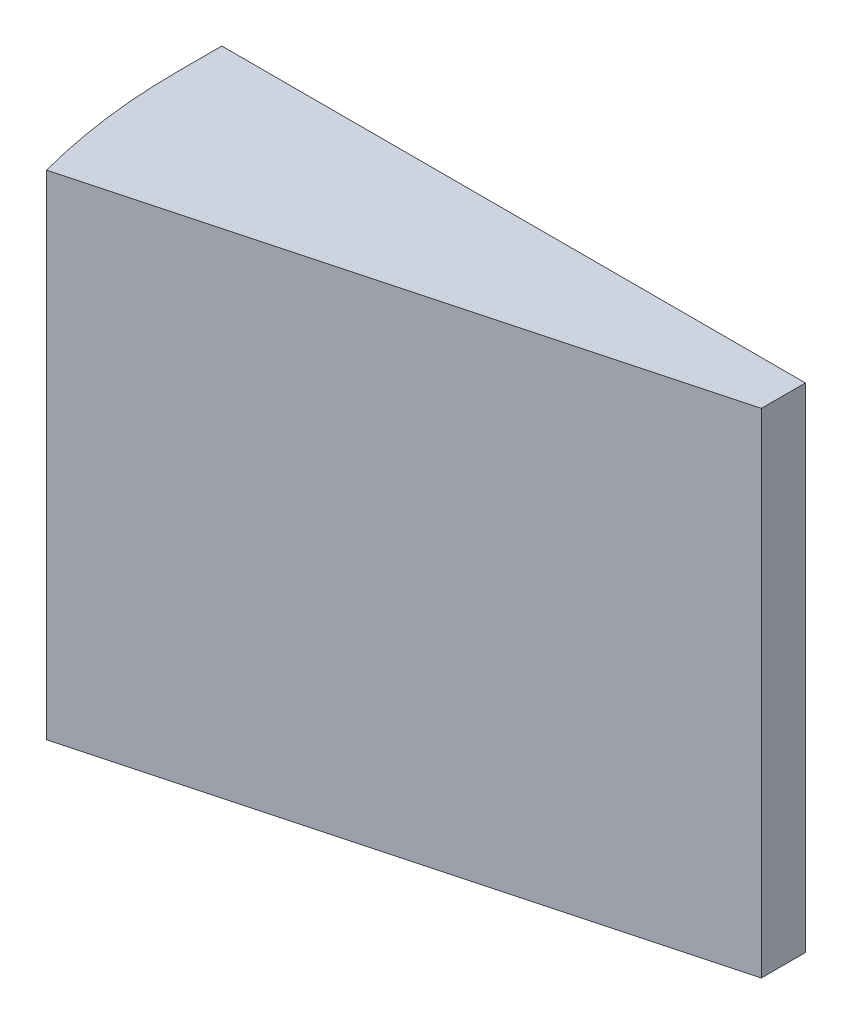
SolidWorks part; units mm, degrees
ref_plane "Front Plane" through (0, 0, 0) normal (0, 0, 1) x (1, 0, 0)
ref_plane "Top Plane" through (0, 0, 0) normal (0, 1, 0) x (1, 0, 0)
ref_plane "Right Plane" through (0, 0, 0) normal (1, 0, 0) x (0, 0, -1)
sketch "Sketch1" plane through (0, 0, 0) normal (0, 0, 1) x (1, 0, 0)
  line L1 (-13.25, 11.2) -> (13.25, 11.2)
  line L2 (-13.25, 11.2) -> (-13.25, -11.2)
  line L3 (-13.25, -11.2) -> (13.25, -11.2)
  line L4 (13.25, 11.2) -> (13.25, -11.2)
  line L5 (-13.25, 11.2) -> (13.25, -11.2) construction
  line L6 (-13.25, -11.2) -> (13.25, 11.2) construction
  point P0 (0, 0)
  dimension "D1" = 22.4
  dimension "D2" = 26.5
extrude "Boss-Extrude1" add sketch "Sketch1" along normal blind 2
sketch "Sketch2" plane through (0, 11.2, 0) normal (0, 1, 0) x (1, 0, 0)
  line L0 (13.25, -2) -> (-12.347, -8.8587)
  line L2 (-13.25, -2) -> (13.25, -2)
  line L4 (-13.25, -2) -> (-13.25, 0) construction
  line L5 (-13.25, -2) -> (-13.25, 0) construction
  arc A1 (-13.25, -2) -> (-12.347, -8.8587) centre (13.25, -2) ccw
  point P3 (0, 0)
  point P5 (-12.6038, -7.8167)
  dimension "D1" = 15
extrude "Boss-Extrude2" add sketch "Sketch2" against normal up to surface (22.4 mm away) up to face at (0, -11.2, 1)
